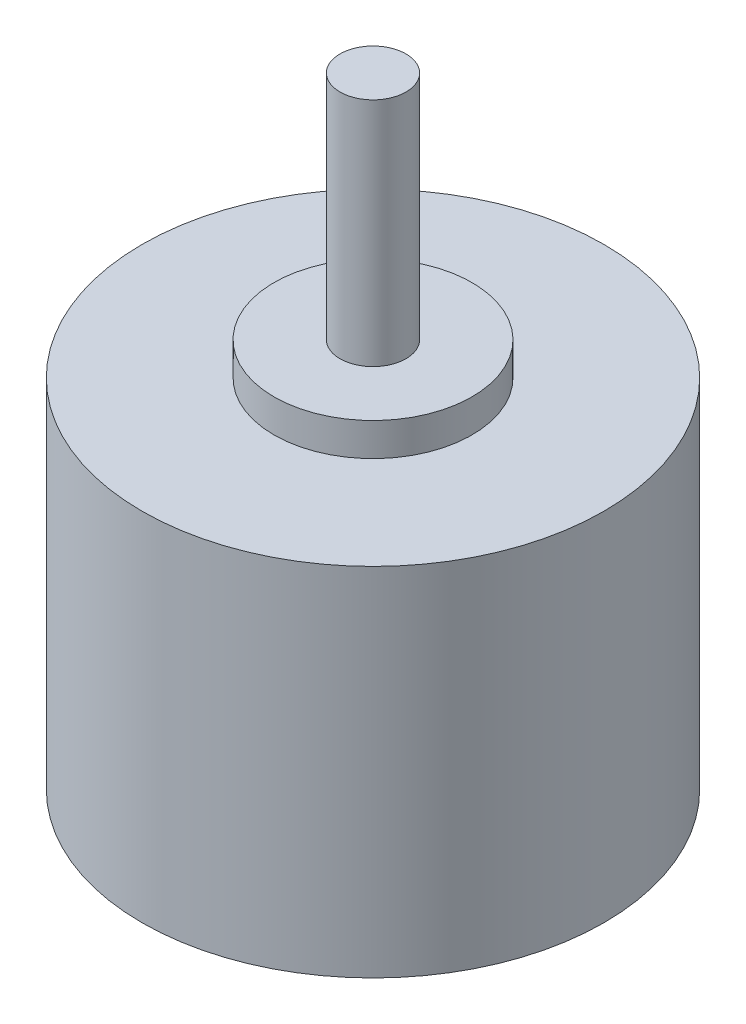
SolidWorks part; units mm, degrees
ref_plane "Plan de face" through (0, 0, 0) normal (0, 0, 1) x (1, 0, 0)
ref_plane "Plan de dessus" through (0, 0, 0) normal (0, 1, 0) x (1, 0, 0)
ref_plane "Plan de droite" through (0, 0, 0) normal (1, 0, 0) x (0, 0, -1)
sketch "Esquisse1" plane through (0, 0, 0) normal (0, 1, 0) x (1, 0, 0)
  circle A0 centre (0, 0) radius 17.5
  dimension "D1" = 35
extrude "Boss.-Extru.1" add sketch "Esquisse1" along normal blind 27
sketch "Esquisse2" plane through (0, 27, 0) normal (0, 1, 0) x (1, 0, 0)
  circle A0 centre (0, 0) radius 7.5
  dimension "D1" = 15
extrude "Boss.-Extru.2" add sketch "Esquisse2" along normal blind 2.5
sketch "Esquisse3" plane through (0, 29.5, 0) normal (0, 1, 0) x (1, 0, 0)
  circle A0 centre (0, 0) radius 2.5
  dimension "D1" = 5
extrude "Boss.-Extru.3" add sketch "Esquisse3" along normal blind 17.5
